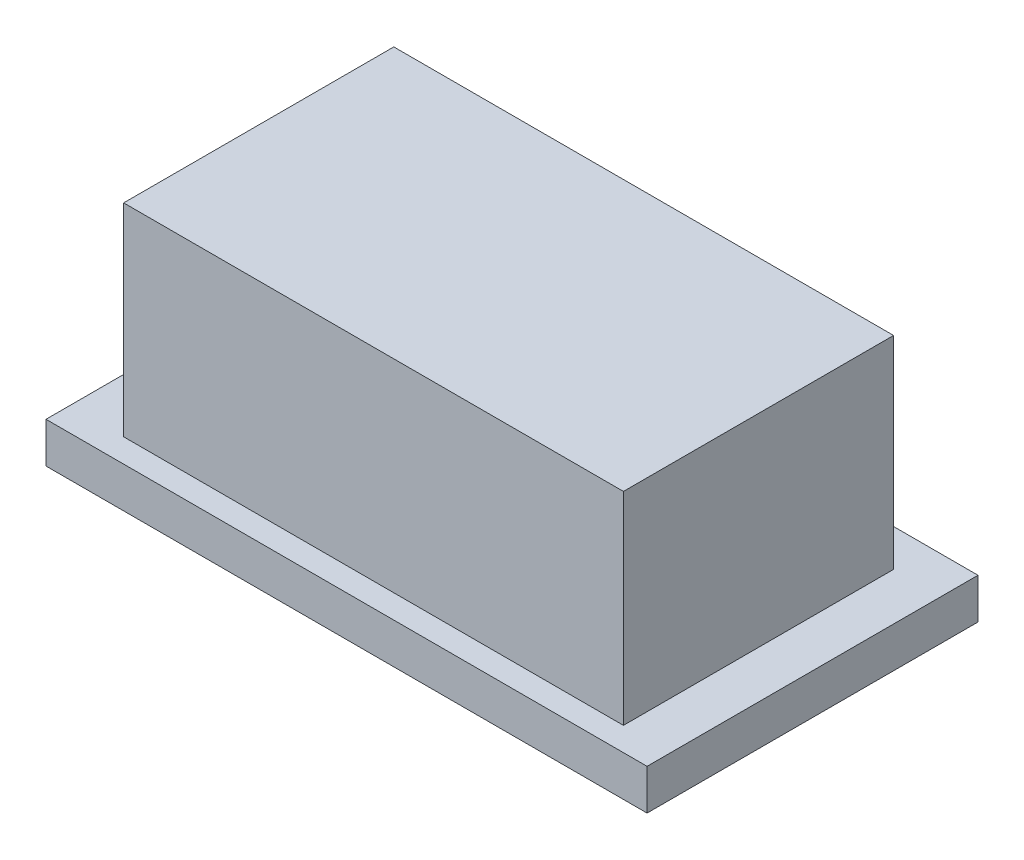
SolidWorks part; units mm, degrees
ref_plane "前视基准面" through (0, 0, 0) normal (0, 0, 1) x (1, 0, 0)
ref_plane "上视基准面" through (0, 0, 0) normal (0, 1, 0) x (1, 0, 0)
ref_plane "右视基准面" through (0, 0, 0) normal (1, 0, 0) x (0, 0, -1)
sketch "草图1" plane through (0, 0, 0) normal (0, 1, 0) x (1, 0, 0)
  line L1 (0, 0) -> (-17.8, 0)
  line L2 (0, 0) -> (0, 9.8)
  line L3 (0, 9.8) -> (-17.8, 9.8)
  line L4 (-17.8, 0) -> (-17.8, 9.8)
extrude "凸台-拉伸1" add sketch "草图1" along normal blind 1.2
sketch "草图2" plane through (0, 1.2, 0) normal (0, 1, 0) x (1, 0, 0)
  line L1 (-1.4, 0.7) -> (-16.2, 0.7)
  line L2 (-1.4, 0.7) -> (-1.4, 8.7)
  line L3 (-1.4, 8.7) -> (-16.2, 8.7)
  line L4 (-16.2, 0.7) -> (-16.2, 8.7)
extrude "凸台-拉伸2" add sketch "草图2" along normal blind 6
